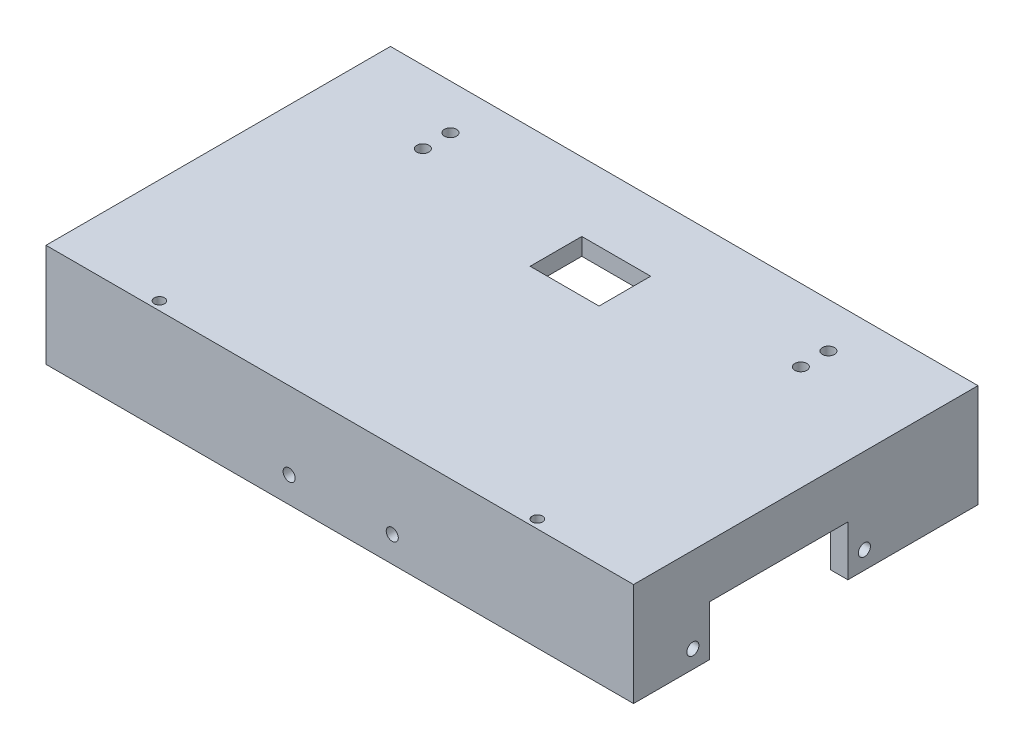
SolidWorks part; units mm, degrees
ref_plane "Front Plane" through (0, 0, 0) normal (0, 0, 1) x (1, 0, 0)
ref_plane "Top Plane" through (0, 0, 0) normal (0, 1, 0) x (1, 0, 0)
ref_plane "Right Plane" through (0, 0, 0) normal (1, 0, 0) x (0, 0, -1)
sketch "Sketch3" plane through (0, 0, 0) normal (0, 1, 0) x (1, 0, 0)
  line L1 (-78.8399, 13.5354) -> (91.7401, 13.5354)
  line L2 (-78.8399, 13.5354) -> (-78.8399, -86.4646)
  line L3 (-78.8399, -86.4646) -> (91.7401, -86.4646)
  line L4 (91.7401, 13.5354) -> (91.7401, -86.4646)
  point P4 (0, 0)
  point P5 (0, 0)
  point P6 (0, 0)
  point P7 (0, 0)
extrude "Boss-Extrude1" add sketch "Sketch3" along normal blind 5
sketch "Sketch4" plane through (0, 5, 0) normal (0, 1, 0) x (1, 0, 0)
  line L0 (91.7401, -86.4646) -> (91.7401, 13.5354)
  line L1 (-78.8399, -86.4646) -> (-78.8399, 13.5354)
  line L2 (-78.8399, 13.5354) -> (-73.8399, 13.5354)
  line L3 (-73.8399, 13.5354) -> (-73.8399, -86.4646)
  line L4 (-73.8399, -86.4646) -> (-78.8399, -86.4646)
  line L5 (91.7401, 13.5354) -> (86.7401, 13.5354)
  line L6 (91.7401, 13.5354) -> (-78.8399, 13.5354) construction
  line L7 (86.7401, 13.5354) -> (86.7401, -86.4646)
  line L8 (-78.8399, -86.4646) -> (91.7401, -86.4646) construction
  line L9 (86.7401, -86.4646) -> (91.7401, -86.4646)
  point P6 (0, 0)
  point P11 (0, 0)
extrude "Boss-Extrude2" add sketch "Sketch4" along normal blind 24.94
sketch "Sketch6" plane through (0, 5, 0) normal (0, 1, 0) x (1, 0, 0)
  line L3 (-73.8399, 13.5354) -> (-73.8399, -86.4646) construction
  line L4 (86.7401, -86.4646) -> (-73.8399, -86.4646)
  line L6 (86.7401, -86.4646) -> (86.7401, -81.4646)
  line L7 (86.7401, -81.4646) -> (-73.8399, -81.4646)
  line L8 (-73.8399, -86.4646) -> (-73.8399, -81.4646)
extrude "Boss-Extrude3" add sketch "Sketch6" along normal blind 24.94
sketch "Sketch7" plane through (0, 5, 0) normal (0, 1, 0) x (1, 0, 0)
  line L0 (6.4501, 13.5354) -> (2.7151, 13.5354)
  line L1 (86.7401, 13.5354) -> (-73.8399, 13.5354) construction
  line L2 (6.4501, 13.5354) -> (10.7151, 13.5354)
  line L3 (10.7151, 13.5354) -> (10.7151, 8.5354)
  line L4 (10.7151, 8.5354) -> (2.7151, 8.5354)
  line L5 (2.7151, 8.5354) -> (2.7151, 13.5354)
extrude "Boss-Extrude4" add sketch "Sketch7" along normal blind 24.94
sketch "Sketch8" plane through (0, 0, -8.5354) normal (0, 0, 1) x (1, 0, 0)
  line L0 (6.7151, 5) -> (6.7151, 29.94) construction
  line L1 (2.7151, 5) -> (10.7151, 5) construction
  line L2 (2.7151, 29.94) -> (10.7151, 29.94) construction
  line L3 (6.7151, 17.47) -> (2.7151, 17.47) construction
  line L4 (2.7151, 29.94) -> (2.7151, 5) construction
  line L5 (6.7151, 5) -> (6.7151, 17.47) construction
  line L6 (6.7151, 17.47) -> (6.7151, 29.94) construction
  circle A0 centre (6.7151, 11.235) radius 1.75
  circle A1 centre (6.7151, 23.705) radius 1.75
extrude "Cut-Extrude1" cut sketch "Sketch8" against normal blind 8
sketch "Sketch9" plane through (-78.8399, 0, 0) normal (-1, 0, 0) x (0, 0, 1)
  line L0 (-13.5354, 29.94) -> (-13.5354, 23.2) construction
  line L1 (-13.5354, 29.94) -> (-13.5354, 0) construction
  line L2 (-13.5354, 23.2) -> (-5.7854, 23.2) construction
  line L3 (-5.7854, 23.2) -> (-5.7854, 29.94) construction
  line L4 (-13.5354, 29.94) -> (86.4646, 29.94) construction
  line L5 (-13.5354, 29.94) -> (-13.5354, 23.2)
  line L6 (-13.5354, 23.2) -> (-5.7854, 23.2)
  line L7 (-5.7854, 23.2) -> (-5.7854, 29.94)
  line L8 (-5.7854, 29.94) -> (-13.5354, 29.94)
extrude "Cut-Extrude2" cut sketch "Sketch9" against normal blind 10
mirror "Mirror1" about plane through (0, 29.94, 0) normal (0, -1, 0) of bodies 115
delete or keep bodies "Body-Delete/Keep 1" type delete bodies bodies 115
sketch "Sketch10" plane through (0, 59.88, 0) normal (0, 1, 0) x (1, 0, 0)
  line L0 (6.4501, 13.5354) -> (6.4501, -6.4646) construction
  line L1 (91.7401, 13.5354) -> (-78.8399, 13.5354) construction
  line L2 (6.4501, -6.4646) -> (-3.2849, -6.4646)
  line L3 (-3.2849, -6.4646) -> (16.7151, -6.4646)
  line L4 (16.7151, -6.4646) -> (16.7151, -21.4646)
  line L5 (16.7151, -21.4646) -> (-3.2849, -21.4646)
  line L6 (-3.2849, -21.4646) -> (-3.2849, -6.4646)
extrude "Cut-Extrude3" cut sketch "Sketch10" against normal blind 10 contours L6 L5 L4 L3 L2
sketch "Sketch11" plane through (0, 59.88, 0) normal (0, 1, 0) x (1, 0, 0)
  circle A0 centre (-48.4199, 0.5354) radius 1.75
  circle A1 centre (-48.4199, -7.4646) radius 1.75
  circle A2 centre (61.3101, -7.4646) radius 1.75
  circle A3 centre (61.3101, 0.5354) radius 1.75
  point P8 (0, 0)
  point P9 (0, 0)
  point P10 (0, 0)
  point P12 (0, 0)
  point P13 (0, 0)
extrude "Cut-Extrude4" cut sketch "Sketch11" against normal blind 10
sketch "Sketch13" plane through (-78.8399, 0, 0) normal (-1, 0, 0) x (0, 0, 1)
  line L0 (-5.7854, 29.94) -> (86.4646, 29.94) construction
  line L1 (86.4646, 29.94) -> (40.3396, 29.94) construction
  line L2 (40.3396, 29.94) -> (64.4396, 29.94) construction
  line L3 (64.4396, 29.94) -> (24.2396, 29.94) construction
  line L4 (24.2396, 29.94) -> (24.2396, 44.505) construction
  line L5 (24.2396, 44.505) -> (64.4396, 44.505) construction
  line L6 (64.4396, 44.505) -> (64.4396, 29.94) construction
  line L7 (24.2396, 44.505) -> (64.4396, 44.505)
  line L8 (64.4396, 44.505) -> (64.4396, 29.94)
  line L9 (64.4396, 29.94) -> (24.2396, 29.94)
  line L10 (24.2396, 29.94) -> (24.2396, 44.505)
extrude "Cut-Extrude6" cut sketch "Sketch13" against normal blind 200
sketch "Sketch14" plane through (-78.8399, 0, 0) normal (-1, 0, 0) x (0, 0, 1)
  circle A0 centre (19.4396, 35.1) radius 1.75
  circle A1 centre (69.2396, 35.1) radius 1.75
extrude "Cut-Extrude7" cut sketch "Sketch14" against normal blind 200
sketch "Sketch15" plane through (0, 59.88, 0) normal (0, 1, 0) x (1, 0, 0)
  line L0 (61.3101, -7.4646) -> (61.3101, -86.4646) construction
  line L1 (-78.8399, -86.4646) -> (91.7401, -86.4646) construction
  line L2 (61.3101, -86.4646) -> (61.3101, -81.4646) construction
  line L3 (-48.4199, -7.4646) -> (-48.4199, -86.4646) construction
  line L4 (-48.4199, -86.4646) -> (-48.4199, -81.4646) construction
  circle A0 centre (61.3101, -83.9646) radius 1.5
  circle A1 centre (-48.4199, -83.9646) radius 1.5
extrude "Cut-Extrude8" cut sketch "Sketch15" against normal blind 10
sketch "Sketch16" plane through (0, 0, 86.4646) normal (0, 0, 1) x (1, 0, 0)
  circle A0 centre (21.6879, 37.44) radius 1.75
  circle A1 centre (-8.2521, 37.44) radius 1.75
extrude "Cut-Extrude9" cut sketch "Sketch16" against normal blind 10
